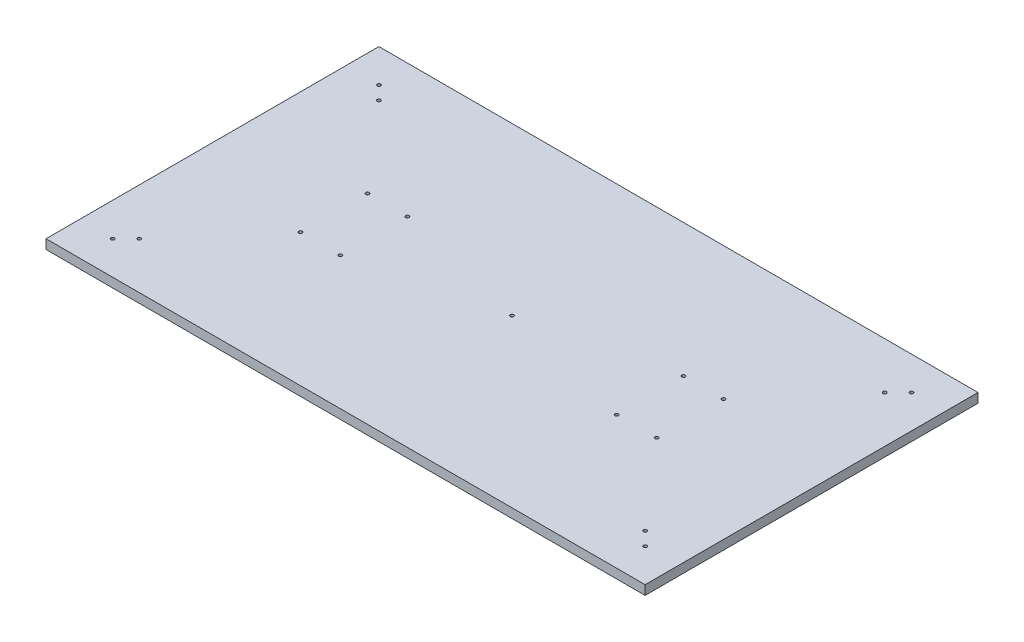
SolidWorks part; units mm, degrees
material "MDF"
ref_plane "Front Plane" through (0, 0, 0) normal (0, 0, 1) x (1, 0, 0)
ref_plane "Top Plane" through (0, 0, 0) normal (0, 1, 0) x (1, 0, 0)
ref_plane "Right Plane" through (0, 0, 0) normal (1, 0, 0) x (0, 0, -1)
sketch "Sketch1" plane through (0, 0, 0) normal (0, 1, 0) x (1, 0, 0)
  line L1 (-450, 250) -> (450, 250)
  line L2 (-450, 250) -> (-450, -250)
  line L3 (-450, -250) -> (450, -250)
  line L4 (450, 250) -> (450, -250)
  line L5 (-450, 250) -> (450, -250) construction
  line L6 (-450, -250) -> (450, 250) construction
  point P0 (0, 0)
  dimension "D1" = 900
  dimension "D2" = 500
extrude "Boss-Extrude1" add sketch "Sketch1" along normal blind 14
sketch "Sketch2" plane through (0, 14, 0) normal (0, 1, 0) x (1, 0, 0)
  line L0 (0, 98.0632) -> (0, 0) construction
  line L8 (-450, -250) -> (-315.6481, -115.6481) construction
  line L9 (-450, -250) -> (450, -250) construction
  circle A0 centre (-207.5, 50.3) radius 2.6
  circle A1 centre (-207.5, -50.3) radius 2.6
  circle A4 centre (0, 0) radius 2.6
  circle A7 centre (-267.5, -50.3) radius 2.6
  circle A8 centre (-267.5, 50.3) radius 2.6
  circle A9 centre (-400, -200) radius 2.6
  circle A10 centre (-380, -180) radius 2.6
  circle A15 centre (-380, 180) radius 2.6
  circle A16 centre (-400, 200) radius 2.6
  circle A25 centre (400, -200) radius 2.6
  circle A26 centre (380, -180) radius 2.6
  circle A27 centre (400, 200) radius 2.6
  circle A28 centre (380, 180) radius 2.6
  circle A29 centre (267.5, 50.3) radius 2.6
  circle A30 centre (267.5, -50.3) radius 2.6
  circle A31 centre (207.5, -50.3) radius 2.6
  circle A32 centre (207.5, 50.3) radius 2.6
  point P0 (0, 0)
  dimension "D3" = 5.2
  dimension "D9" = 5.2
  dimension "D6" = 45
  dimension "D7" = 50
  dimension "D8" = 70
extrude "Cut-Extrude1" cut sketch "Sketch2" against normal blind 10
